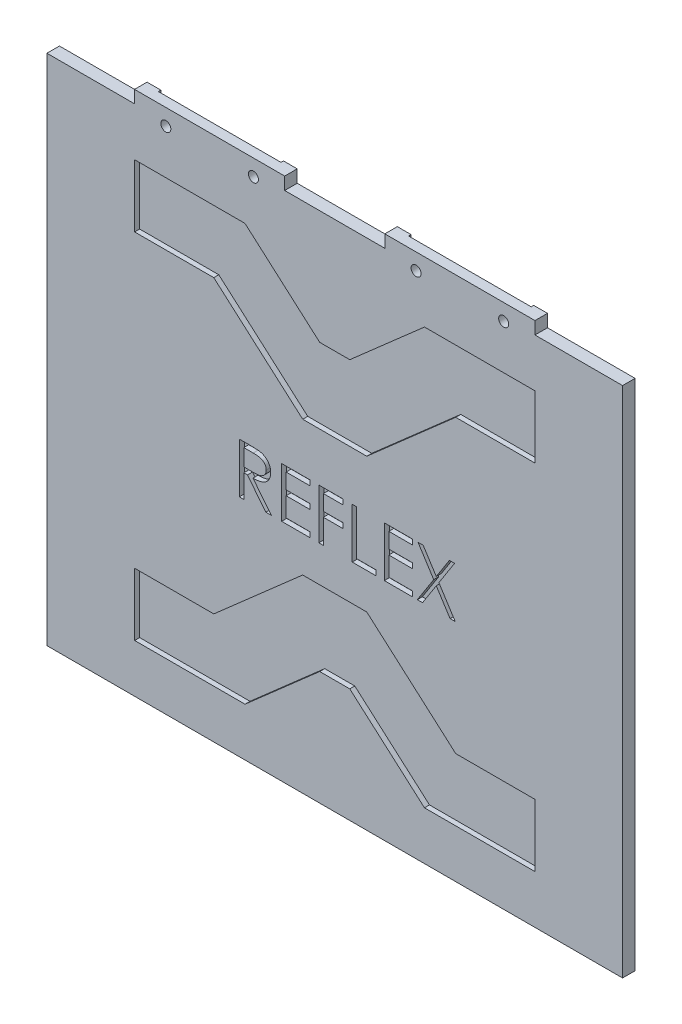
SolidWorks part; units mm, degrees
ref_plane "Plan de face" through (0, 0, 0) normal (0, 0, 1) x (1, 0, 0)
ref_plane "Plan de dessus" through (0, 0, 0) normal (0, 1, 0) x (1, 0, 0)
ref_plane "Plan de droite" through (0, 0, 0) normal (1, 0, 0) x (0, 0, -1)
sketch "Esquisse1" plane through (0, 0, 0) normal (0, 0, 1) x (1, 0, 0)
  line L0 (-56, 10.1029) -> (-21, 10.1029)
  line L1 (-21, 10.1029) -> (-21, 15.1029)
  line L2 (-21, 15.1029) -> (39, 15.1029)
  line L3 (39, 15.1029) -> (39, 10.1029)
  line L4 (39, 10.1029) -> (79, 10.1029)
  line L5 (79, 10.1029) -> (79, 15.1029)
  line L6 (79, 15.1029) -> (139, 15.1029)
  line L7 (139, 15.1029) -> (139, 10.1029)
  line L8 (139, 10.1029) -> (174, 10.1029)
  line L9 (174, 10.1029) -> (174, -194.8971)
  line L11 (-56, -194.8971) -> (-56, 10.1029)
  line L12 (-56, -194.8971) -> (174, -194.8971)
  dimension "D1" = 35
  dimension "D2" = 60
  dimension "D3" = 40
  dimension "D4" = 60
  dimension "D6" = 35
  dimension "D7" = 205
  dimension "D8" = 205
  dimension "D9" = 5
  dimension "D10" = 5
  dimension "D11" = 5
extrude "Boss.-Extru.1" add sketch "Esquisse1" along normal blind 5
sketch "Esquisse2" plane through (0, 0, 5) normal (0, 0, 1) x (1, 0, 0)
  line L12 (-20.9506, -9.2143) -> (23.1449, -9.2143)
  line L13 (23.1449, -9.2143) -> (52.9979, -35.4433)
  line L14 (52.9979, -35.4433) -> (65.7016, -35.4433)
  line L15 (-20.9506, -9.2143) -> (-20.9506, -34.2143)
  line L16 (-20.9506, -34.2143) -> (10.6592, -34.2143)
  line L17 (10.6592, -34.2143) -> (46.203, -65.4433)
  line L18 (46.203, -65.4433) -> (66.9072, -65.4433)
  line L21 (71.797, -65.4433) -> (51.0928, -65.4433)
  line L22 (65.0021, -35.4433) -> (52.2984, -35.4433)
  line L23 (94.8551, -9.2143) -> (65.0021, -35.4433)
  line L24 (138.9506, -9.2143) -> (94.8551, -9.2143)
  line L25 (138.9506, -9.2143) -> (138.9506, -34.2143)
  line L26 (138.9506, -34.2143) -> (107.3408, -34.2143)
  line L27 (107.3408, -34.2143) -> (71.797, -65.4433)
  line L30 (-20.9506, -150.5798) -> (10.6592, -150.5798)
  line L31 (10.6592, -150.5798) -> (46.203, -119.3508)
  line L32 (46.203, -119.3508) -> (66.9072, -119.3508)
  line L33 (71.797, -119.3508) -> (51.0928, -119.3508)
  line L34 (107.3408, -150.5798) -> (71.797, -119.3508)
  line L35 (138.9506, -150.5798) -> (107.3408, -150.5798)
  line L36 (138.9506, -175.5798) -> (138.9506, -150.5798)
  line L37 (138.9506, -175.5798) -> (94.8551, -175.5798)
  line L38 (94.8551, -175.5798) -> (65.0021, -149.3508)
  line L39 (52.9979, -149.3508) -> (65.7016, -149.3508)
  line L40 (23.1449, -175.5798) -> (52.9979, -149.3508)
  line L41 (-20.9506, -175.5798) -> (23.1449, -175.5798)
  line L42 (-20.9506, -175.5798) -> (-20.9506, -150.5798)
  text T0 "REFLEX" font "Century Gothic" height 20
  point P28 (51.0928, -119.3508)
  dimension "D1" = 25
  dimension "D2" = 30
extrude "Enlèv. mat.-Extru.2" cut sketch "Esquisse2" against normal blind 2
sketch "Esquisse3" plane through (0, 0, 5) normal (0, 0, 1) x (1, 0, 0)
  text T0 "REFLEX" font "Century Gothic" height 20
extrude "Enlèv. mat.-Extru.3" cut sketch "Esquisse3" against normal blind 2
sketch "Esquisse4" plane through (0, 0, 0) normal (0, 0, -1) x (-1, 0, 0)
  line L0 (15.5, 15.1029) -> (15.5, 2.5835)
  line L1 (-39, 15.1029) -> (21, 15.1029) construction
  line L2 (15.5, 2.5835) -> (-33.5, 2.5835)
  line L3 (-33.5, 2.5835) -> (-33.5, 15.1029)
  line L4 (-59, 31.8183) -> (-59, -50.6761) construction
  line L5 (-84.5, 2.5835) -> (-84.5, 15.1029)
  line L6 (-133.5, 15.1029) -> (-133.5, 2.5835)
  line L7 (-133.5, 2.5835) -> (-84.5, 2.5835)
  line L8 (-84.5, 15.1029) -> (-133.5, 15.1029)
  line L9 (15.5, 15.1029) -> (-33.5, 15.1029)
  dimension "D1" = 49
  dimension "D2" = 5.5
extrude "Enlèv. mat.-Extru.5" cut sketch "Esquisse4" against normal blind 1 contours L9 L3 L2 L0 | L8 L6 L7 L5
sketch "Esquisse5" plane through (0, 0, 0) normal (0, 0, -1) x (-1, 0, 0)
  line L0 (15.5, 15.1029) -> (15.5, 2.5835) construction
  line L1 (15.5, 2.5835) -> (-33.5, 2.5835) construction
  line L2 (-9, 2.5835) -> (-9, 30.371) construction
  line L3 (15.5, 2.5835) -> (-33.5, 2.5835) construction
  line L4 (-59, 30.371) -> (-59, -23.1779) construction
  circle A0 centre (8.5, 8.5835) radius 2
  circle A1 centre (-26.5, 8.5835) radius 2
  circle A2 centre (-126.5, 8.5835) radius 2
  circle A3 centre (-91.5, 8.5835) radius 2
  dimension "D1" = 4
  dimension "D2" = 7
  dimension "D3" = 6
extrude "Enlèv. mat.-Extru.6" cut sketch "Esquisse5" against normal through all
